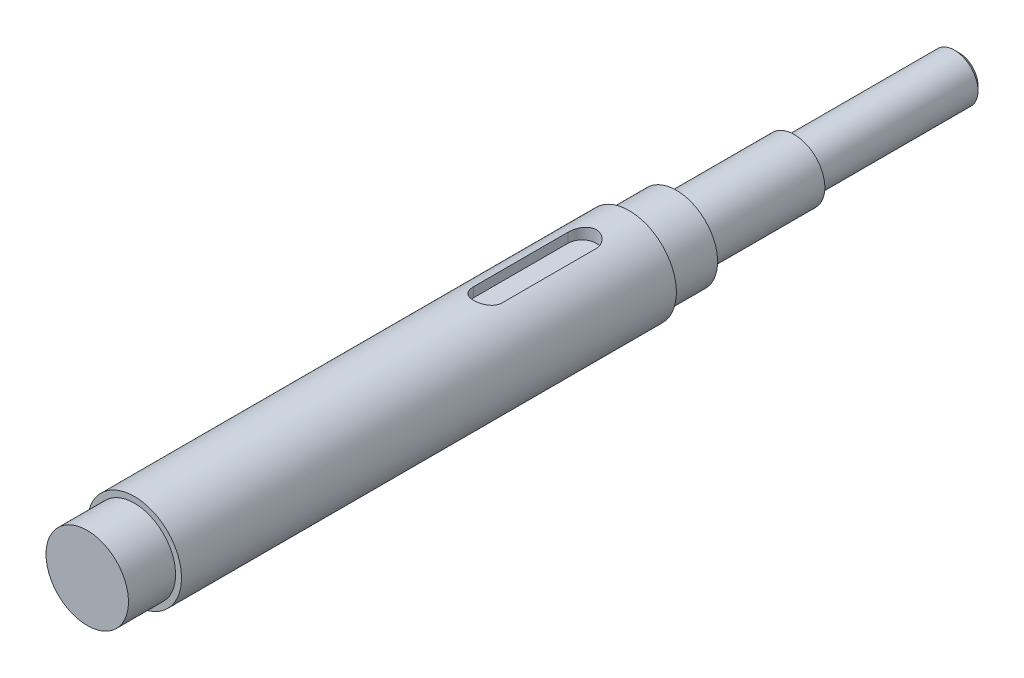
SolidWorks part; units mm, degrees
ref_plane "Front Plane" through (0, 0, 0) normal (0, 0, 1) x (1, 0, 0)
ref_plane "Top Plane" through (0, 0, 0) normal (0, 1, 0) x (1, 0, 0)
ref_plane "Right Plane" through (0, 0, 0) normal (1, 0, 0) x (0, 0, -1)
sketch "Sketch1" plane through (0, 0, 0) normal (0, 1, 0) x (1, 0, 0)
  line L0 (0, 0) -> (0, -370)
  line L1 (0, 0) -> (10, 0)
  line L2 (10, 0) -> (10, -70)
  line L3 (10, -70) -> (13, -70)
  line L4 (13, -70) -> (13, -120)
  line L5 (13, -120) -> (17.5, -120)
  line L6 (17.5, -120) -> (17.5, -140)
  line L7 (17.5, -140) -> (20, -140)
  line L8 (20, -140) -> (20, -350)
  line L9 (20, -350) -> (17.5, -350)
  line L10 (17.5, -350) -> (17.5, -370)
  line L11 (17.5, -370) -> (0, -370)
  dimension "D1" = 370
  dimension "D2" = 70
  dimension "D3" = 50
  dimension "D4" = 20
  dimension "D5" = 10
  dimension "D6" = 3
  dimension "D7" = 4.5
  dimension "D8" = 20
revolve "Revolve1" add sketch "Sketch1" angle 360 about L0
sketch "Sketch2" plane through (15.1264, 34.1957, 140) normal (0, 0, -1) x (-1, 0, 0)
  line L0 (15.1264, -14.1957) -> (15.1264, -34.1957) construction
  line L1 (15.1264, -34.1957) -> (15.1264, -14.1957) construction
  circle A0 centre (15.1264, -34.1957) radius 20 construction
  circle A2 centre (15.1264, -34.1957) radius 20
  dimension "Angle from vertical" = 360
ref_plane "Plane1" through (0, 20, 140) normal (0, -1, 0) x (-1, 0, 0)
sketch "Sketch3" plane through (-7.5632, 20, 140) normal (0, -1, 0) x (0, 0, -1)
  line L0 (-20, 7.5632) -> (-60, 7.5632) construction
  line L1 (-20, 13.5632) -> (-60, 13.5632)
  line L2 (-20, 1.5632) -> (-60, 1.5632)
  arc A0 (-20, 13.5632) -> (-20, 1.5632) centre (-20, 7.5632) cw
  arc A1 (-60, 13.5632) -> (-60, 1.5632) centre (-60, 7.5632) ccw
  dimension "Keyway width" = 12
  dimension "Distance from end face" = 20
  dimension "Length of slot" = 40
extrude "Cut-Extrude1" cut sketch "Sketch3" along normal blind 5
other "keyway (bs 4235 - part i)<1>"
chamfer "Chamfer1" distance 2 angle 45 1 edges at (-10, 0, 0)
